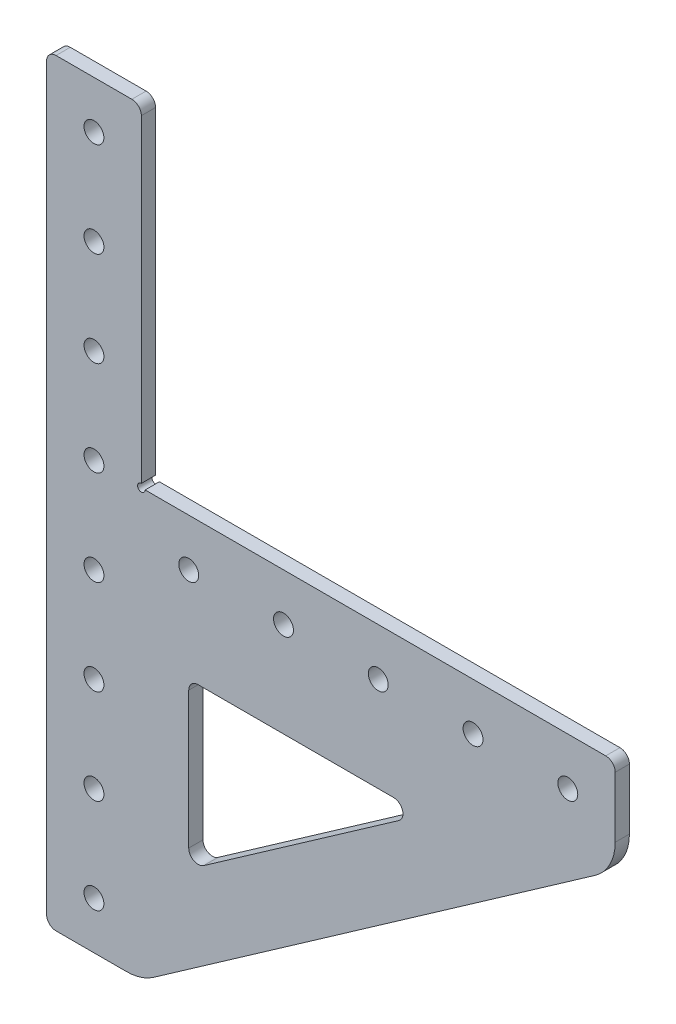
SolidWorks part; units mm, degrees
material "Thornel Mat VMA"
ref_plane "Front Plane" through (0, 0, 0) normal (0, 0, 1) x (1, 0, 0)
ref_plane "Top Plane" through (0, 0, 0) normal (0, 1, 0) x (1, 0, 0)
ref_plane "Right Plane" through (0, 0, 0) normal (1, 0, 0) x (0, 0, -1)
sketch "Sketch1" plane through (0, 0, 0) normal (0, 0, 1) x (1, 0, 0)
  line L0 (0, 0) -> (-110, 0) construction
  line L1 (-110, -80) -> (-110, 80) construction
  line L2 (-100, -80) -> (-100, -10)
  line L3 (0, 10) -> (-100, 10)
  line L4 (-120, -80) -> (-120, 80)
  line L5 (0, -10) -> (-100, -10)
  line L6 (-100, -80) -> (-120, -80)
  line L7 (-100, 80) -> (-120, 80)
  line L8 (0, 10) -> (0, -10)
  line L10 (0, 10) -> (-110, 10) construction
  line L11 (-100, 10) -> (-100, 80)
  line L12 (-100, -80) -> (-100, 80) construction
  line L13 (0, -10) -> (-110, -10) construction
  circle A0 centre (-110, 70) radius 2.1
  circle A1 centre (-110, 50) radius 2.1
  circle A2 centre (-110, 30) radius 2.1
  circle A3 centre (-110, 10) radius 2.1
  circle A4 centre (-110, -10) radius 2.1
  circle A5 centre (-110, -30) radius 2.1
  circle A6 centre (-110, -50) radius 2.1
  circle A7 centre (-110, -70) radius 2.1
  circle A8 centre (-10, 0) radius 2.1
  circle A9 centre (-30, 0) radius 2.1
  circle A10 centre (-50, 0) radius 2.1
  circle A11 centre (-70, 0) radius 2.1
  circle A12 centre (-90, 0) radius 2.1
  point P6 (-110, 0)
  dimension "D5" = 4.2
  dimension "D6" = 10
  dimension "D8" = 20
  dimension "D9" = 10
  dimension "D11" = 20
  dimension "D1" = 160
  dimension "D2" = 110
  dimension "D3" = 10
  dimension "D4" = 10
  dimension "D7" = 8
  dimension "D10" = 5
extrude "Boss-Extrude1" add sketch "Sketch1" along normal blind 3
fillet "Fillet1" radius 2 6 edges at (-120, -80, 1.5) (-100, 80, 1.5) (0, 10, 1.5) (0, -10, 1.5) (-100, -80, 1.5) (-120, 80, 1.5)
sketch "Sketch3" plane through (0, 0, 3) normal (0, 0, 1) x (1, 0, 0)
  circle A0 centre (-100, 10) radius 0.8
  circle A1 centre (-100, -10) radius 0.8
  dimension "D1" = 1.6
extrude "Cut-Extrude1" cut sketch "Sketch3" against normal through all
sketch "Sketch4" plane through (0, 0, 0) normal (0, 0, -1) x (-1, 0, 0)
  line L0 (0, -8) -> (0, -10)
  line L2 (0, -10) -> (100, -80)
  line L3 (100, -80) -> (102, -80)
  line L4 (100, -78) -> (100, -10.8)
  line L5 (99.2, -10) -> (2, -10)
  arc A0 (0, -8) -> (2, -10) centre (2, -8) ccw construction
  arc A1 (100, -10.8) -> (99.2, -10) centre (100, -10) ccw construction
  arc A2 (100, -78) -> (102, -80) centre (102, -78) ccw construction
  arc A3 (100, -10.8) -> (99.2, -10) centre (100, -10) ccw
  arc A4 (100, -78) -> (102, -80) centre (102, -78) ccw
  arc A5 (0, -8) -> (2, -10) centre (2, -8) ccw
extrude "Boss-Extrude2" add sketch "Sketch4" against normal up to surface (3 mm away) up to face at (-80.2189, 0, 3)
sketch "Sketch5" plane through (0, 0, 0) normal (0, 0, -1) x (-1, 0, 0)
  line L1 (40.4426, -20) -> (90, -20)
  line L2 (8.6019, 2.2885) -> (108.6019, -67.7115)
  line L3 (40.4426, -20) -> (90, -54.6902)
  line L4 (90, -20) -> (90, -54.6902)
  circle A0 centre (110, -30) radius 2.1 construction
  circle A1 centre (70, 0) radius 2.1 construction
  point P2 (94.8084, -11.045)
  dimension "D2" = 20
  dimension "D3" = 20
  dimension "D1" = 15
extrude "Cut-Extrude2" cut sketch "Sketch5" against normal through all
fillet "Fillet2" radius 2 3 edges at (-90, -54.6902, 1.5) (-40.4426, -20, 1.5) (-90, -20, 1.5)
fillet "Fillet3" radius 10 2 edges at (-100, -80, 1.5) (0, -10, 1.5)
